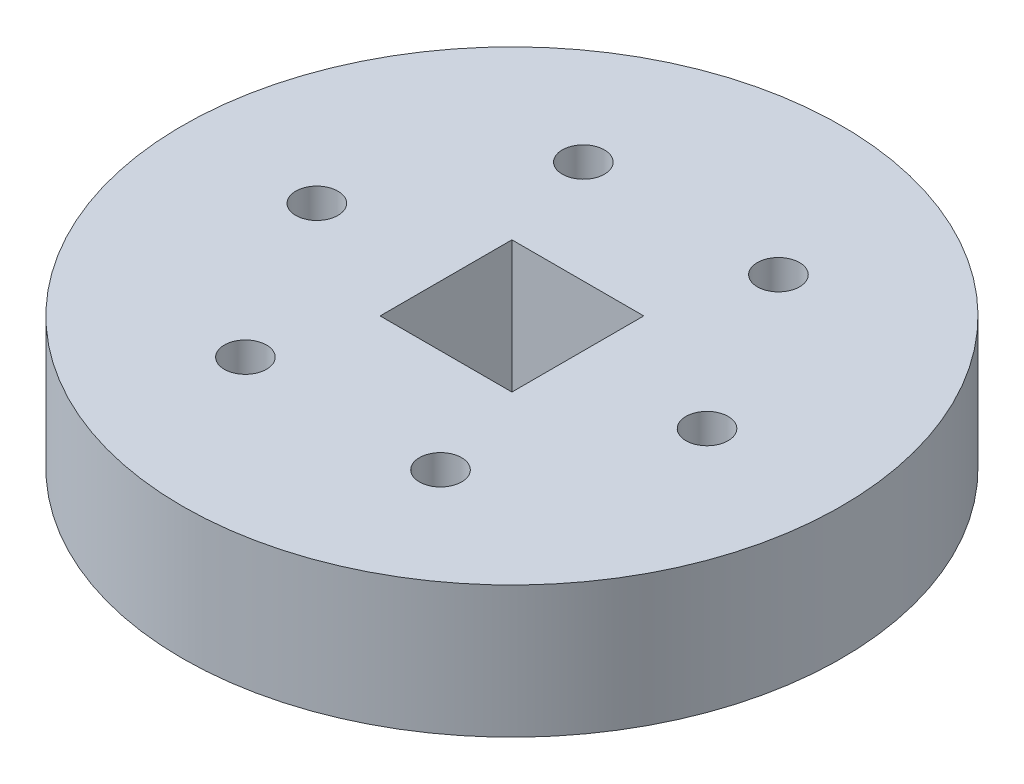
SolidWorks part; units mm, degrees
ref_plane "Front Plane" through (0, 0, 0) normal (0, 0, 1) x (1, 0, 0)
ref_plane "Top Plane" through (0, 0, 0) normal (0, 1, 0) x (1, 0, 0)
ref_plane "Right Plane" through (0, 0, 0) normal (1, 0, 0) x (0, 0, -1)
sketch "Elevator Support Pulleys" plane through (0, 0, 0) normal (0, 1, 0) x (1, 0, 0)
  line L0 (-15.875, 0) -> (15.875, 0) construction
  line L1 (-3.175, 3.175) -> (3.175, 3.175)
  line L2 (-3.175, 3.175) -> (-3.175, -3.175)
  line L3 (-3.175, -3.175) -> (3.175, -3.175)
  line L4 (3.175, 3.175) -> (3.175, -3.175)
  line L5 (-3.175, 3.175) -> (3.175, -3.175) construction
  line L6 (-3.175, -3.175) -> (3.175, 3.175) construction
  circle A0 centre (0, 0) radius 15.875
  circle A1 centre (9.398, 0) radius 1.016
  circle A2 centre (4.699, -8.1389) radius 1.016
  circle A3 centre (-4.699, -8.1389) radius 1.016
  circle A4 centre (-9.398, 0) radius 1.016
  circle A5 centre (-4.699, 8.1389) radius 1.016
  circle A6 centre (4.699, 8.1389) radius 1.016
  point P23 (0, 0)
  dimension "D1" = 31.75
  dimension "D3" = 2.032
  dimension "D4" = 9.398
  dimension "D2" = 6.35
  dimension "D5" = 6
extrude "Boss-Extrude1" add sketch "Elevator Support Pulleys" along normal blind 6.35
equation "\"Ball Diameter\"= 1.75in"
equation "\"Sheet Thickness\"= 0.25in"
equation "\"Screw Diameter\"= .17in"
equation "\"Robot Diameter\"= 14in"
equation "\"Castor Screw Diameter\"= 0.22in"
equation "\"Wheel Diameter\" = 4in"
equation "\"Nut Diameter\" = 8.4mm"
equation "\"Nut Height\" = 2.9mm"
equation "\"Screw Height\" = 0.55in"
equation "\"Pulley Diameter\" = 1in"
equation "\"Reactor Height\" = 14in"
equation "\"Elevator Height\" = 11.5in"
equation "\"Elevator Width\" = \"Ball Diameter\" + 0.25in"
equation "\"Elevator Axle Length\" = \"Elevator Width\" + 8*\"Sheet Thickness\""
equation "\"D1@Elevator Support Pulleys\"=\"Elevator Axle Endcap Diameter\""
equation "\"D2@Elevator Support Pulleys\"=\"Sheet Thickness\""
equation "\"D1@Boss-Extrude1\"=\"Sheet Thickness\""
equation "\"Elevator Bearing Diameter\" = sqr(2*(\"Sheet Thickness\"^2)) + 0.2in"
equation "\"Elevator Axle Endcap Diameter\" = \"Pulley Diameter\" + 0.25in"
